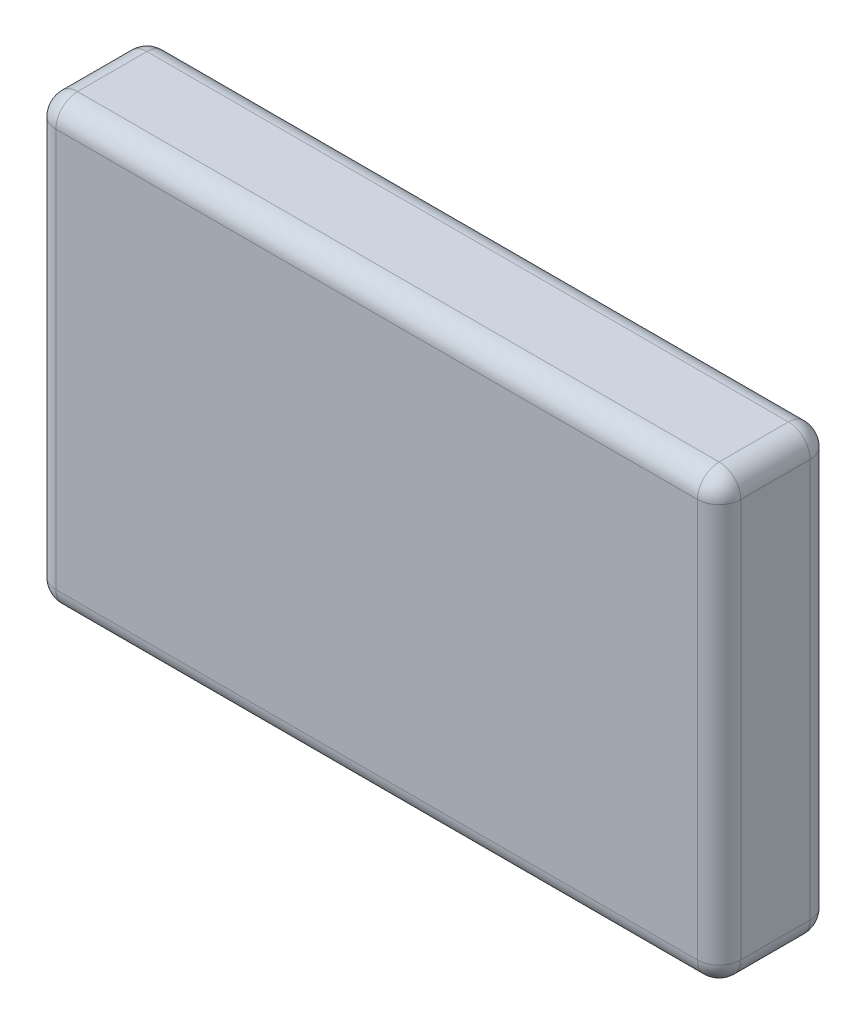
SolidWorks part; units mm, degrees
material "ABS PC"
ref_plane "Plan de face" through (0, 0, 0) normal (0, 0, 1) x (1, 0, 0)
ref_plane "Plan de dessus" through (0, 0, 0) normal (0, 1, 0) x (1, 0, 0)
ref_plane "Plan de droite" through (0, 0, 0) normal (1, 0, 0) x (0, 0, -1)
sketch "Esquisse1" plane through (0, 0, 0) normal (0, 0, 1) x (1, 0, 0)
  line L1 (0, 0) -> (-158, 0)
  line L2 (0, 0) -> (0, 102)
  line L3 (0, 102) -> (-158, 102)
  line L4 (-158, 0) -> (-158, 102)
  dimension "D1" = 158
  dimension "D2" = 102
extrude "Boss.-Extru.1" add sketch "Esquisse1" along normal blind 26
fillet "Congé1" radius 5 12 edges at (-158, 102, 13) (-79, 102, 26) (0, 0, 13) (0, 51, 26) (-158, 51, 26) (-79, 0, 26) (-158, 0, 13) (0, 102, 13) (0, 51, 0) (-79, 102, 0) (-158, 51, 0) (-79, 0, 0)
